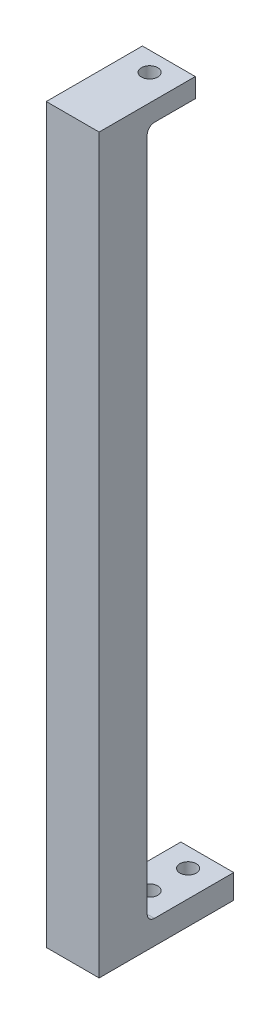
SolidWorks part; units mm, degrees
ref_plane "Front Plane" through (0, 0, 0) normal (0, 0, 1) x (1, 0, 0)
ref_plane "Top Plane" through (0, 0, 0) normal (0, 1, 0) x (1, 0, 0)
ref_plane "Right Plane" through (0, 0, 0) normal (1, 0, 0) x (0, 0, -1)
sketch "Sketch1" plane through (0, 0, 0) normal (0, 1, 0) x (1, 0, 0)
  line L1 (-5.5, 5) -> (5.5, 5)
  line L2 (-5.5, 5) -> (-5.5, -5)
  line L3 (-5.5, -5) -> (5.5, -5)
  line L4 (5.5, 5) -> (5.5, -5)
  line L5 (-5.5, 5) -> (5.5, -5) construction
  line L6 (-5.5, -5) -> (5.5, 5) construction
  point P0 (0, 0)
  dimension "D1" = 10
  dimension "D2" = 11
extrude "Boss-Extrude1" add sketch "Sketch1" along normal mid plane 152.4
sketch "Sketch3" plane through (0, 76.2, 0) normal (0, 1, 0) x (1, 0, 0)
  line L0 (0, 15) -> (0, -5) construction
  line L1 (5.5, 15) -> (-5.5, 15)
  line L14 (-5.5, -5) -> (5.5, -5) construction
  line L16 (5.5, -5) -> (5.5, 5) construction
  line L17 (5.5, 15) -> (5.5, -5)
  line L18 (5.5, -5) -> (-5.5, -5)
  line L19 (-5.5, 15) -> (-5.5, -5)
  line L20 (-5.5, 5) -> (-5.5, -5) construction
  line L21 (-7, 5) -> (7, 5) construction
  circle A6 centre (0, 11) radius 1.7
  dimension "D1" = 20
  dimension "D2" = 4
  dimension "D3" = 3.4
extrude "Boss-Extrude3" add sketch "Sketch3" against normal blind 4
sketch "Sketch4" plane through (0, -76.2, 0) normal (0, -1, 0) x (1, 0, 0)
  line L0 (5.5, 5) -> (5.5, -5) construction
  line L1 (-5.5, 5) -> (5.5, 5)
  line L2 (-5.5, 5) -> (-5.5, -23)
  line L3 (-5.5, -23) -> (5.5, -23)
  line L4 (5.5, 5) -> (5.5, -23)
  circle A0 centre (0, -11) radius 1.7 construction
  circle A1 centre (0, -11) radius 1.7
  circle A2 centre (0, -19) radius 1.7
  dimension "D1" = 8
  dimension "D2" = 4
extrude "Boss-Extrude4" add sketch "Sketch4" against normal blind 5
fillet "Fillet1" radius 1.5 2 edges at (0, 72.2, -5) (0, -71.2, -5)
